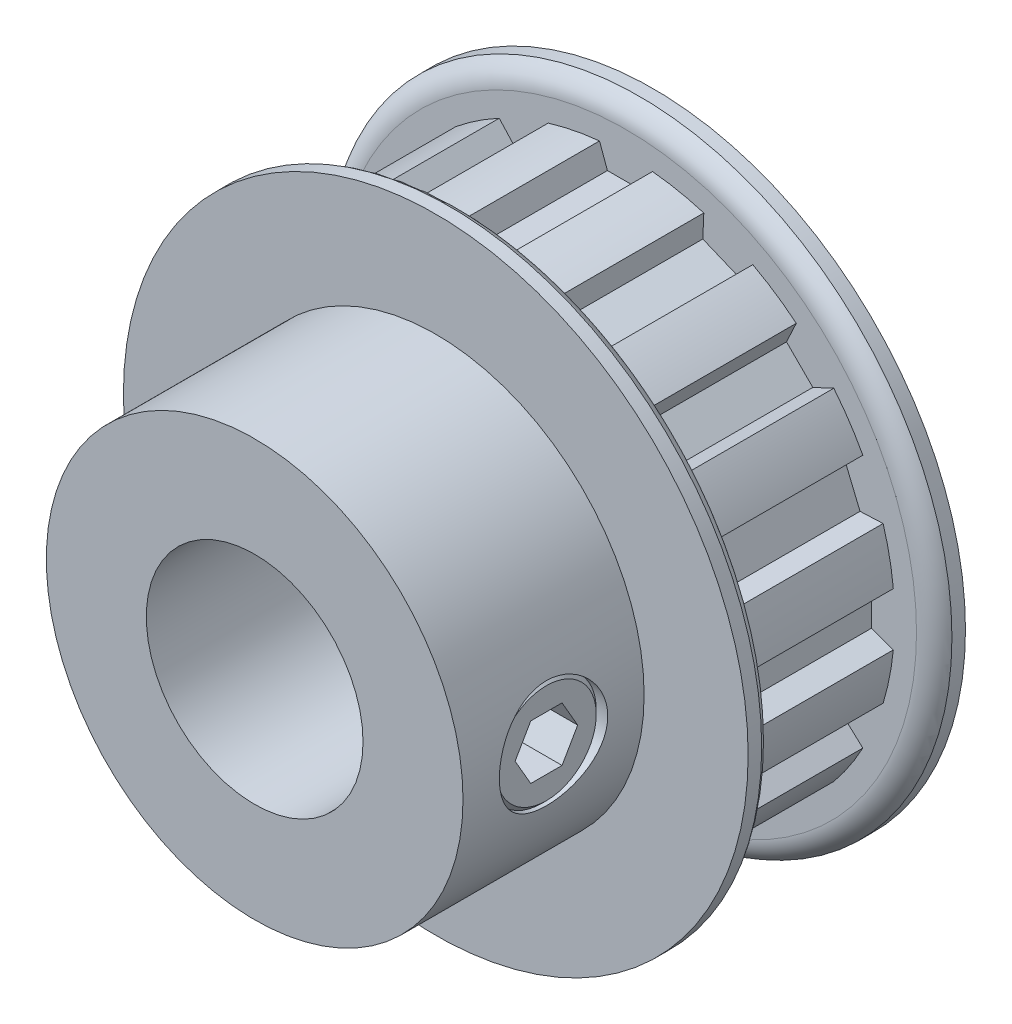
SolidWorks part; units mm, degrees
ref_plane "Front Plane" through (0, 0, 0) normal (0, 0, 1) x (1, 0, 0)
ref_plane "Top Plane" through (0, 0, 0) normal (0, 1, 0) x (1, 0, 0)
ref_plane "Right Plane" through (0, 0, 0) normal (1, 0, 0) x (0, 0, -1)
sketch "Sketch1" plane through (0, 0, 0) normal (0, 0, 1) x (1, 0, 0)
  line L0 (-2.3241, 23.4315) -> (-1.6307, 21.5265)
  line L1 (-1.6307, 21.5265) -> (1.6307, 21.5265)
  line L2 (1.6307, 21.5265) -> (2.3241, 23.4315)
  line L3 (-2.3241, 23.4315) -> (2.3241, 23.4315)
  line L4 (0, 0) -> (0, 21.5265) construction
  line L5 (0, 21.5265) -> (0, 25.0825) construction
  circle A0 centre (0, 0) radius 24.257 construction
  circle A1 centre (0, 0) radius 27.3812 construction
  circle A2 centre (0, 0) radius 23.5465 construction
  point P6 (0, 23.4315)
  point P11 (0, 24.257)
  point P13 (0, 27.3812)
  point P14 (0, 23.5465)
  dimension "D1" = 1.651
  dimension "D2" = 0.8255
sketch "Sketch2" plane through (0, 0, 0) normal (1, 0, 0) x (0, 0, -1)
  line L0 (-17.4625, 9.5) -> (17.4625, 9.5)
  line L1 (-17.4625, 9.5) -> (-17.4625, 18.2626)
  line L2 (-17.4625, 18.2626) -> (-1.5875, 18.2626)
  line L3 (-1.5875, 18.2626) -> (-1.5875, 27.3812)
  line L4 (-1.5875, 27.3812) -> (0.7874, 27.3812) construction
  line L5 (0.7874, 27.3812) -> (0.7874, 23.5465) construction
  line L6 (0.7874, 23.5465) -> (15.0876, 23.5465)
  line L7 (15.0876, 23.5465) -> (15.0876, 27.3812) construction
  line L8 (15.0876, 27.3812) -> (17.4625, 27.3812) construction
  line L9 (17.4625, 27.3812) -> (17.4625, 9.5)
  line L10 (-17.4625, 0) -> (17.4625, 0) construction
  line L13 (-1.5875, 27.3812) -> (-0.4001, 27.3812)
  line L14 (0.7874, 25.4638) -> (0.7874, 23.5465)
  line L15 (15.0876, 23.5465) -> (15.0876, 25.4638)
  line L16 (16.2751, 27.3812) -> (17.4625, 27.3812)
  arc A0 (0.7874, 25.4638) -> (-0.4001, 27.3812) centre (-1.3543, 25.4638) ccw
  arc A1 (15.0876, 25.4638) -> (16.2751, 27.3812) centre (17.2293, 25.4638) cw
  point P12 (0.7874, 25.4638)
  point P14 (-0.4001, 27.3812)
  point P20 (15.0876, 25.4638)
  point P21 (16.2751, 27.3812)
  point P25 (15.0876, 0)
  point P26 (0.7874, 0)
  dimension "Bore" = 19
  dimension "Hub Dia" = 36.5252
  dimension "Outside Width" = 19.05
  dimension "Inside Width" = 14.3002
revolve "Revolve1" add sketch "Sketch2" angle 360 mid plane about L10
sketch "Sketch3" plane through (0, 0, 0) normal (0, 0, 1) x (1, 0, 0)
  line L0 (-1.6307, 21.5265) -> (1.6307, 21.5265) construction
  line L1 (1.6307, 21.5265) -> (2.3241, 23.4315) construction
  line L2 (-2.3241, 23.4315) -> (-1.6307, 21.5265) construction
  line L3 (-1.6307, 21.5265) -> (1.6307, 21.5265)
  line L4 (1.6307, 21.5265) -> (2.3241, 23.4315)
  line L5 (-2.3241, 23.4315) -> (-1.6307, 21.5265)
  circle A0 centre (0, 0) radius 23.5465 construction
  arc A1 (2.3241, 23.4315) -> (-2.3241, 23.4315) centre (0, 0) ccw
extrude "Cut-Extrude1" cut sketch "Sketch3" against normal up to vertex (15.0876 mm away) from vertex at -0.7874 starting at point (0, 23.5465, -0.7874)
pattern_circular "CirPattern1" count 16 over 360 about axis through (0, 0, 0) along (0, 0, 1) of "Cut-Extrude1"
sketch "Sketch4" plane through (0, 0, 0) normal (1, 0, 0) x (0, -1, 0)
  line L0 (0, -1.5875) -> (0, -17.4625) construction
  line L1 (-18.2626, -1.5875) -> (18.2626, -1.5875) construction
  line L2 (-18.2626, -17.4625) -> (18.2626, -17.4625) construction
  circle A0 centre (0, -9.525) radius 4.75
  dimension "D1" = 9.5
extrude "Cut-Extrude2" cut sketch "Sketch4" along normal through all
ref_plane "Plane1" through (0, 0, 9.525) normal (0, 0, 1) x (1, 0, 0)
sketch "Sketch5" plane through (0, 0, 9.525) normal (0, 0, 1) x (1, 0, 0)
  line L0 (0, 0.1664) -> (0, 18.2626) construction
  line L1 (9.5, -4.369) -> (9.5, 0)
  line L2 (9.881, -4.75) -> (17.2531, -4.75)
  line L3 (9.5, 0) -> (18.2626, 0) construction
  line L4 (9.5, 0) -> (17.6341, 0)
  line L5 (17.6341, 0) -> (17.6341, -4.369)
  line L6 (9.881, -4.75) -> (9.5, -4.369)
  line L7 (17.6341, -4.369) -> (17.2531, -4.75)
  circle A0 centre (0, 0) radius 18.2626 construction
  circle A1 centre (0, 0) radius 9.5 construction
  point P2 (9.5, -4.75)
  point P11 (17.6341, -4.75)
revolve "Revolve2" add sketch "Sketch5" angle 360 mid plane about L4
sketch "Sketch6" plane through (17.6341, 5.3841, 0) normal (-1, 0, 0) x (0, -1, 0)
  line L1 (5.3841, 12.2674) -> (3.0091, 10.8962)
  line L2 (3.0091, 10.8962) -> (3.0091, 8.1538)
  line L3 (3.0091, 8.1538) -> (5.3841, 6.7826)
  line L4 (5.3841, 6.7826) -> (7.7591, 8.1538)
  line L5 (7.7591, 8.1538) -> (7.7591, 10.8962)
  line L6 (7.7591, 10.8962) -> (5.3841, 12.2674)
  circle A0 centre (5.3841, 9.525) radius 2.375 construction
  dimension "D1" = 4.75
extrude "Cut-Extrude3" cut sketch "Sketch6" along normal blind 3.5625
equation "\"D2@Sketch1\" = \"D1@Sketch1\"/2"
equation "\"D1@Sketch4\" = \"Bore@Sketch2\"/2"
equation "\"D1@Sketch6\" = \"D1@Sketch4\"/2"
equation "\"D1@Cut-Extrude3\" = \"D1@Sketch6\"*.75"
